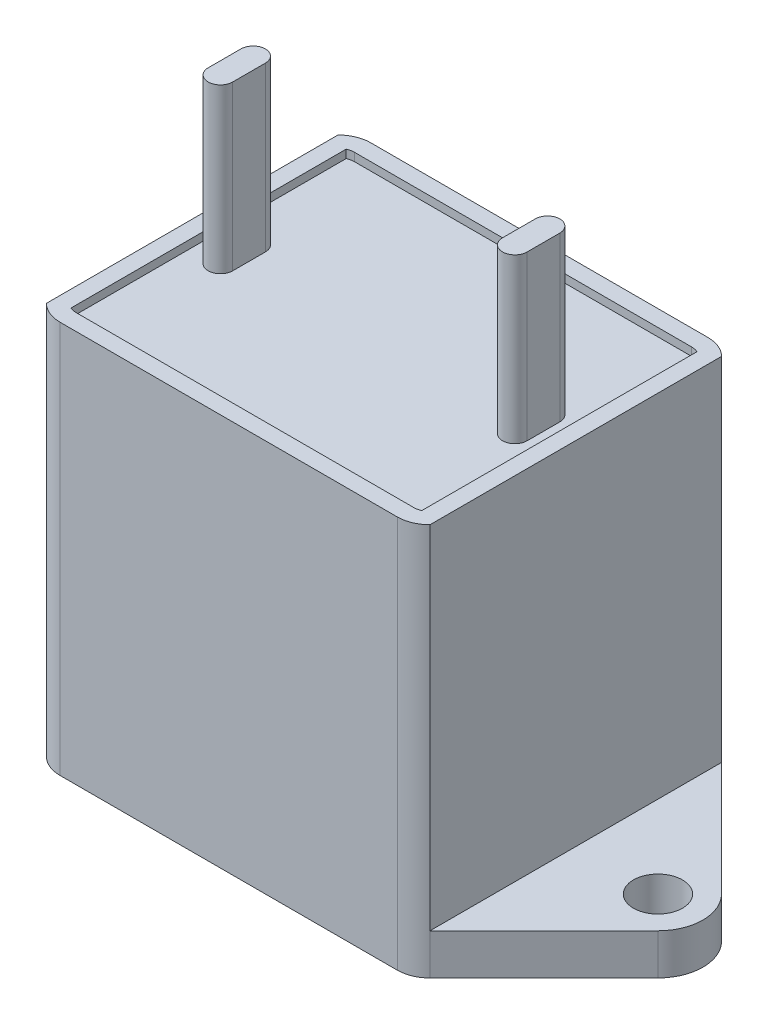
SolidWorks part; units mm, degrees
ref_plane "Front Plane" through (0, 0, 0) normal (0, 0, 1) x (1, 0, 0)
ref_plane "Top Plane" through (0, 0, 0) normal (0, 1, 0) x (1, 0, 0)
ref_plane "Right Plane" through (0, 0, 0) normal (1, 0, 0) x (0, 0, -1)
sketch "Sketch1" plane through (0, 0, 0) normal (0, 1, 0) x (1, 0, 0)
  line L0 (-19.5, 0) -> (19.5, 0) construction
  line L1 (-19.5, 9.5) -> (19.5, 9.5)
  line L2 (-19.5, 9.5) -> (-19.5, -9.5)
  line L3 (-19.5, -9.5) -> (19.5, -9.5)
  line L4 (19.5, 9.5) -> (19.5, -9.5)
  line L5 (-19.5, 9.5) -> (19.5, -9.5) construction
  line L6 (-19.5, -9.5) -> (19.5, 9.5) construction
  line L7 (-18.6945, 1.9445) -> (-11.1391, 9.5)
  line L8 (-18.6945, -1.9445) -> (-11.1391, -9.5)
  line L9 (0, 9.5) -> (0, -9.5) construction
  line L10 (18.6945, -1.9445) -> (11.1391, -9.5)
  line L11 (18.6945, 1.9445) -> (11.1391, 9.5)
  circle A0 centre (-16.75, 0) radius 2.75
  circle A1 centre (16.75, 0) radius 2.75
  circle A2 centre (-16.75, 0) radius 1.5
  circle A3 centre (16.75, 0) radius 1.5
  point P0 (0, 0)
  dimension "D3" = 33.5
  dimension "D5" = 3
  dimension "D1" = 39
  dimension "D2" = 19
  dimension "D4" = 45
extrude "Boss-Extrude1" add sketch "Sketch1" along normal blind 2.5 contours L10 A1 L11 L1 L7 A0 L8 L3 | A0 A2 | A1 A3
fillet "Fillet1" radius 2 4 edges at (-11.1391, 1.25, -9.5) (11.1391, 1.25, -9.5) (11.1391, 1.25, 9.5) (-11.1391, 1.25, 9.5)
sketch "Sketch3" plane through (0, 2.5, 0) normal (0, 1, 0) x (1, 0, 0)
  line L1 (-11.7249, 9.5) -> (11.7249, 9.5)
  line L2 (-11.7249, 9.5) -> (-11.7249, -9.5)
  line L3 (-11.7249, -9.5) -> (11.7249, -9.5)
  line L4 (11.7249, 9.5) -> (11.7249, -9.5)
  line L6 (10.3107, 9.5) -> (-10.3107, 9.5)
  line L7 (-11.7249, 8.9142) -> (-18.6945, 1.9445)
  line L8 (-18.6945, -1.9445) -> (-11.7249, -8.9142)
  line L9 (-10.3107, -9.5) -> (10.3107, -9.5)
  line L10 (11.7249, -8.9142) -> (18.6945, -1.9445)
  line L11 (18.6945, 1.9445) -> (11.7249, 8.9142)
  line L12 (10.3107, 9.5) -> (-10.3107, 9.5)
  line L13 (-11.7249, 8.9142) -> (-18.6945, 1.9445)
  line L14 (-18.6945, -1.9445) -> (-11.7249, -8.9142)
  line L15 (-10.3107, -9.5) -> (10.3107, -9.5)
  line L16 (11.7249, -8.9142) -> (18.6945, -1.9445)
  line L17 (18.6945, 1.9445) -> (11.7249, 8.9142)
  arc A6 (-10.3107, 9.5) -> (-11.7249, 8.9142) centre (-10.3107, 7.5) ccw
  arc A7 (-18.6945, 1.9445) -> (-18.6945, -1.9445) centre (-16.75, 0) ccw
  arc A8 (-11.7249, -8.9142) -> (-10.3107, -9.5) centre (-10.3107, -7.5) ccw
  arc A9 (10.3107, -9.5) -> (11.7249, -8.9142) centre (10.3107, -7.5) ccw
  arc A10 (18.6945, -1.9445) -> (18.6945, 1.9445) centre (16.75, 0) ccw
  arc A11 (11.7249, 8.9142) -> (10.3107, 9.5) centre (10.3107, 7.5) ccw
  arc A12 (-10.3107, 9.5) -> (-11.7249, 8.9142) centre (-10.3107, 7.5) ccw
  arc A13 (-18.6945, 1.9445) -> (-18.6945, -1.9445) centre (-16.75, 0) ccw
  arc A14 (-11.7249, -8.9142) -> (-10.3107, -9.5) centre (-10.3107, -7.5) ccw
  arc A15 (10.3107, -9.5) -> (11.7249, -8.9142) centre (10.3107, -7.5) ccw
  arc A16 (18.6945, -1.9445) -> (18.6945, 1.9445) centre (16.75, 0) ccw
  arc A17 (11.7249, 8.9142) -> (10.3107, 9.5) centre (10.3107, 7.5) ccw
  line M17 (10.3107, 9.5) -> (-10.3107, 9.5)
  arc M18 (-10.3107, 9.5) -> (-11.7249, 8.9142) centre (-10.3107, 7.5) ccw
  arc M22 (-11.7249, -8.9142) -> (-10.3107, -9.5) centre (-10.3107, -7.5) ccw
  line M23 (-10.3107, -9.5) -> (10.3107, -9.5)
  arc M24 (10.3107, -9.5) -> (11.7249, -8.9142) centre (10.3107, -7.5) ccw
  arc M28 (11.7249, 8.9142) -> (10.3107, 9.5) centre (10.3107, 7.5) ccw
  dimension "D1" = 0
extrude "Boss-Extrude2" add sketch "Sketch3" along normal offset from surface (21.5 mm away) 24 contours L4 L2 M28 M17 M18 M22 M23 M24 up to face at (0, 0, 0)
sketch "Sketch4" plane through (0, 24, 0) normal (0, 1, 0) x (1, 0, 0)
  line L8 (10.7249, -8.4102) -> (10.7249, 8.4102)
  line L9 (10.3107, 8.5) -> (-10.3107, 8.5)
  line L10 (-10.7249, 8.4102) -> (-10.7249, -8.4102)
  line L11 (-10.3107, -8.5) -> (10.3107, -8.5)
  line L12 (10.7249, -8.4102) -> (10.7249, 8.4102)
  line L13 (10.3107, 8.5) -> (-10.3107, 8.5)
  line L14 (-10.7249, 8.4102) -> (-10.7249, -8.4102)
  line L15 (-10.3107, -8.5) -> (10.3107, -8.5)
  arc A8 (10.7249, 8.4102) -> (10.3107, 8.5) centre (10.3107, 7.5) ccw
  arc A9 (-10.3107, 8.5) -> (-10.7249, 8.4102) centre (-10.3107, 7.5) ccw
  arc A10 (-10.7249, -8.4102) -> (-10.3107, -8.5) centre (-10.3107, -7.5) ccw
  arc A11 (10.3107, -8.5) -> (10.7249, -8.4102) centre (10.3107, -7.5) ccw
  arc A12 (10.7249, 8.4102) -> (10.3107, 8.5) centre (10.3107, 7.5) ccw
  arc A13 (-10.3107, 8.5) -> (-10.7249, 8.4102) centre (-10.3107, 7.5) ccw
  arc A14 (-10.7249, -8.4102) -> (-10.3107, -8.5) centre (-10.3107, -7.5) ccw
  arc A15 (10.3107, -8.5) -> (10.7249, -8.4102) centre (10.3107, -7.5) ccw
  dimension "D1" = 1
extrude "Cut-Extrude1" cut sketch "Sketch4" against normal blind 0.5
sketch "Sketch5" plane through (0, 23.5, 0) normal (0, 1, 0) x (1, 0, 0)
  line L0 (-10.7249, 0) -> (10.7249, 0) construction
  line L1 (-10.7249, 8.4102) -> (-10.7249, -8.4102) construction
  line L2 (10.7249, -8.4102) -> (10.7249, 8.4102) construction
  line L3 (-9, 1) -> (-9, -1) construction
  line L4 (-8.25, 1) -> (-8.25, -1)
  line L5 (-9.75, 1) -> (-9.75, -1)
  line L6 (0, 8.5) -> (0, -8.5) construction
  line L7 (10.3107, 8.5) -> (-10.3107, 8.5) construction
  line L8 (-10.3107, -8.5) -> (10.3107, -8.5) construction
  line L9 (9, 1) -> (9, -1) construction
  line L10 (8.25, 1) -> (8.25, -1)
  line L11 (9.75, 1) -> (9.75, -1)
  arc A0 (-8.25, 1) -> (-9.75, 1) centre (-9, 1) ccw
  arc A1 (-9.75, -1) -> (-8.25, -1) centre (-9, -1) ccw
  arc A2 (8.25, 1) -> (9.75, 1) centre (9, 1) cw
  arc A3 (9.75, -1) -> (8.25, -1) centre (9, -1) cw
  point P8 (-9, 0)
  point P21 (9, 0)
  dimension "D1" = 2
  dimension "D2" = 1.5
  dimension "D3" = 18
extrude "Boss-Extrude3" add sketch "Sketch5" along normal blind 10
